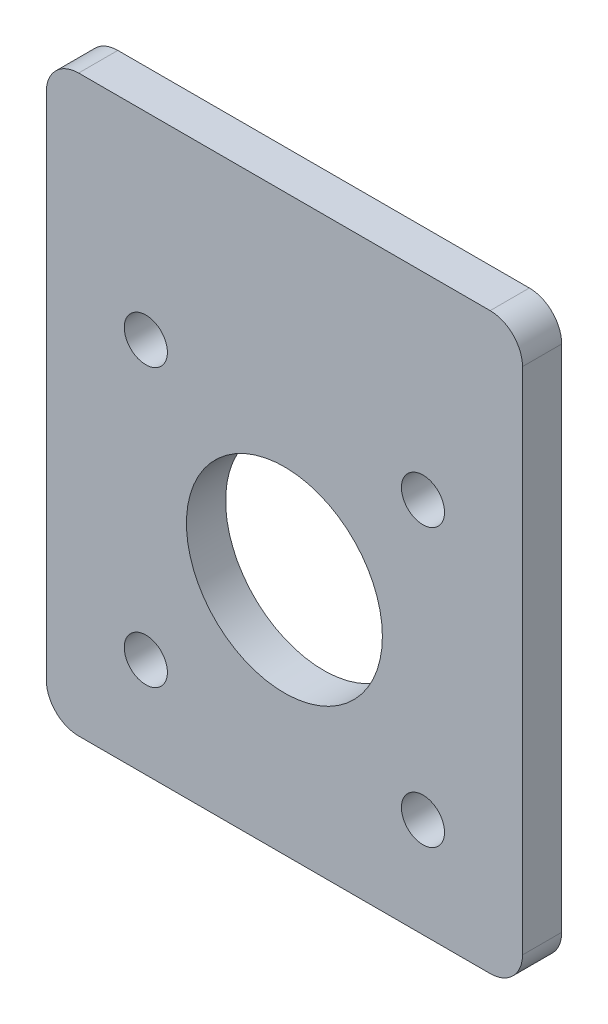
SolidWorks part; units mm, degrees
material "Thornel Mat VMA"
ref_plane "Alzado" through (0, 0, 0) normal (0, 0, 1) x (1, 0, 0)
ref_plane "Planta" through (0, 0, 0) normal (0, 1, 0) x (1, 0, 0)
ref_plane "Vista lateral" through (0, 0, 0) normal (1, 0, 0) x (0, 0, -1)
sketch "Croquis1" plane through (0, 0, 0) normal (0, 0, 1) x (1, 0, 0)
  line L4 (-18.5432, 4.0117) -> (-18.5432, -21.9883)
  line L5 (-16.5432, -23.9883) -> (4.4568, -23.9883)
  line L6 (6.4568, -21.9883) -> (6.4568, 4.0117)
  line L7 (4.4568, 6.0117) -> (-16.5432, 6.0117)
  circle A9 centre (-6.0432, -11.4883) radius 5
  arc A10 (-18.5432, -21.9883) -> (-16.5432, -23.9883) centre (-16.5432, -21.9883) ccw
  arc A11 (4.4568, -23.9883) -> (6.4568, -21.9883) centre (4.4568, -21.9883) ccw
  arc A12 (6.4568, 4.0117) -> (4.4568, 6.0117) centre (4.4568, 4.0117) ccw
  arc A13 (-16.5432, 6.0117) -> (-18.5432, 4.0117) centre (-16.5432, 4.0117) ccw
  circle A14 centre (-13.1143, -4.4173) radius 1.1
  circle A15 centre (1.0278, -4.4173) radius 1.1
  circle A16 centre (-13.1143, -18.5594) radius 1.1
  circle A17 centre (1.0278, -18.5594) radius 1.1
  circle A18 centre (-6.0432, -11.4883) radius 10 construction
  dimension "D1" = 30
  dimension "D2" = 25
  dimension "D3" = 14.1421
  dimension "D4" = 14.1421
  dimension "D5" = 2.2
  dimension "D6" = 2.2
  dimension "D7" = 2.2
  dimension "D8" = 2.2
  dimension "D9" = 10
  dimension "D13" = 2
  dimension "D14" = 2
  dimension "D15" = 2
  dimension "D16" = 2
  dimension "D17" = 2
  dimension "D10" = 30
  dimension "D11" = 25
  dimension "D12" = 12.5
  dimension "D18" = 2
extrude "Saliente-Extruir1" add sketch "Croquis1" along normal blind 2
sketch "Croquis2" plane through (0, 0, 2) normal (0, 0, 1) x (1, 0, 0)
  line L8 (-18.1932, 4.0117) -> (-18.1932, -21.9883)
  line L9 (-16.5432, -23.6383) -> (4.4568, -23.6383)
  line L10 (6.1068, -21.9883) -> (6.1068, 4.0117)
  line L11 (4.4568, 5.6617) -> (-16.5432, 5.6617)
  line L12 (-18.1932, 4.0117) -> (-18.1932, -21.9883)
  line L13 (-16.5432, -23.6383) -> (4.4568, -23.6383)
  line L14 (6.1068, -21.9883) -> (6.1068, 4.0117)
  line L15 (4.4568, 5.6617) -> (-16.5432, 5.6617)
  line L20 (4.4568, 6.0117) -> (-16.5432, 6.0117)
  line L21 (6.4568, -21.9883) -> (6.4568, 4.0117)
  line L22 (-16.5432, -23.9883) -> (4.4568, -23.9883)
  line L23 (-18.5432, 4.0117) -> (-18.5432, -21.9883)
  line L24 (4.4568, 6.0117) -> (-16.5432, 6.0117)
  line L25 (6.4568, -21.9883) -> (6.4568, 4.0117)
  line L26 (-16.5432, -23.9883) -> (4.4568, -23.9883)
  line L27 (-18.5432, 4.0117) -> (-18.5432, -21.9883)
  arc A8 (-16.5432, 5.6617) -> (-18.1932, 4.0117) centre (-16.5432, 4.0117) ccw
  arc A9 (-18.1932, -21.9883) -> (-16.5432, -23.6383) centre (-16.5432, -21.9883) ccw
  arc A10 (4.4568, -23.6383) -> (6.1068, -21.9883) centre (4.4568, -21.9883) ccw
  arc A11 (6.1068, 4.0117) -> (4.4568, 5.6617) centre (4.4568, 4.0117) ccw
  arc A12 (-16.5432, 5.6617) -> (-18.1932, 4.0117) centre (-16.5432, 4.0117) ccw
  arc A13 (-18.1932, -21.9883) -> (-16.5432, -23.6383) centre (-16.5432, -21.9883) ccw
  arc A14 (4.4568, -23.6383) -> (6.1068, -21.9883) centre (4.4568, -21.9883) ccw
  arc A15 (6.1068, 4.0117) -> (4.4568, 5.6617) centre (4.4568, 4.0117) ccw
  arc A20 (-16.5432, 6.0117) -> (-18.5432, 4.0117) centre (-16.5432, 4.0117) ccw
  arc A21 (6.4568, 4.0117) -> (4.4568, 6.0117) centre (4.4568, 4.0117) ccw
  arc A22 (4.4568, -23.9883) -> (6.4568, -21.9883) centre (4.4568, -21.9883) ccw
  arc A23 (-18.5432, -21.9883) -> (-16.5432, -23.9883) centre (-16.5432, -21.9883) ccw
  arc A24 (-16.5432, 6.0117) -> (-18.5432, 4.0117) centre (-16.5432, 4.0117) ccw
  arc A25 (6.4568, 4.0117) -> (4.4568, 6.0117) centre (4.4568, 4.0117) ccw
  arc A26 (4.4568, -23.9883) -> (6.4568, -21.9883) centre (4.4568, -21.9883) ccw
  arc A27 (-18.5432, -21.9883) -> (-16.5432, -23.9883) centre (-16.5432, -21.9883) ccw
  dimension "D1" = 0.35
  dimension "D2" = 0
extrude "Cortar-Extruir1" cut sketch "Croquis2" against normal up to surface (2 mm away) up to face at (-6.0432, -8.9883, 0)
